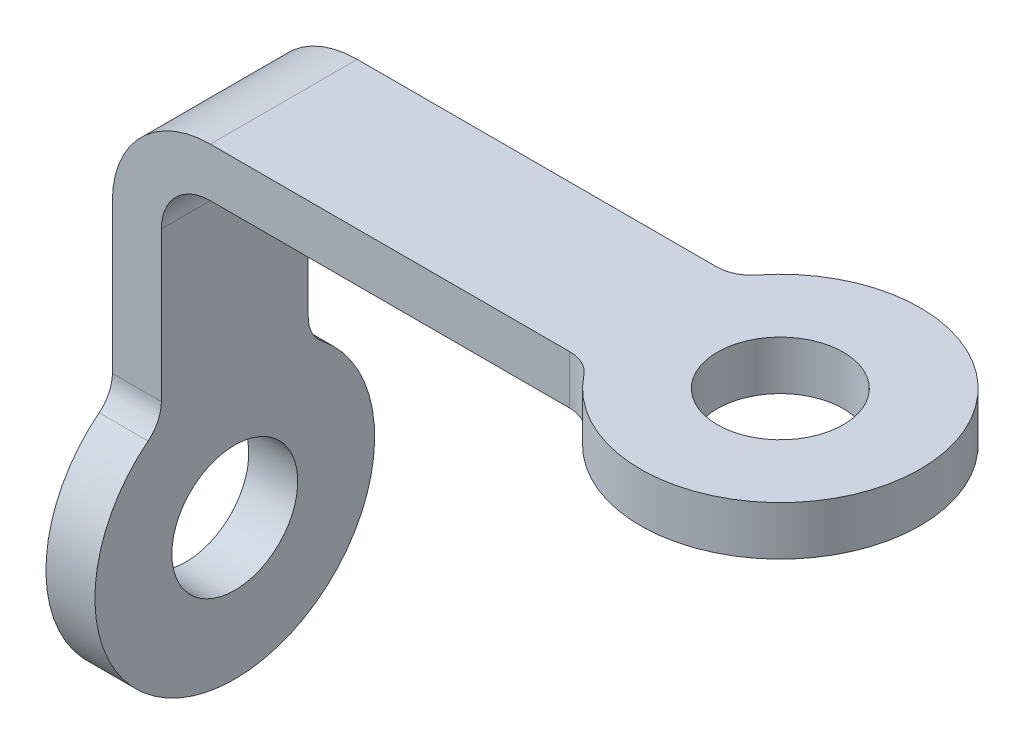
SolidWorks part; units mm, degrees
ref_plane "Front Plane" through (0, 0, 0) normal (0, 0, 1) x (1, 0, 0)
ref_plane "Top Plane" through (0, 0, 0) normal (0, 1, 0) x (1, 0, 0)
ref_plane "Right Plane" through (0, 0, 0) normal (1, 0, 0) x (0, 0, -1)
sketch "Sketch1" plane through (0, 0, 0) normal (0, 1, 0) x (1, 0, 0)
  line L0 (-19.615, 10.5) -> (-85, 10.5)
  line L1 (-19.615, -10.5) -> (-85, -10.5)
  line L2 (0, 0) -> (-86.4775, 0) construction
  line L3 (-85, 10.5) -> (-85, -10.5)
  circle A0 centre (0, 0) radius 9
  arc A1 (-15.692, -12.4) -> (-15.692, 12.4) centre (0, 0) ccw
  arc A2 (-19.615, -10.5) -> (-15.692, -12.4) centre (-19.615, -15.5) cw
  arc A3 (-19.615, 10.5) -> (-15.692, 12.4) centre (-19.615, 15.5) ccw
  point P3 (-68.0925, -10.5)
  dimension "D1" = 21
  dimension "D2" = 40
  dimension "D3" = 18
  dimension "D4" = 5
  dimension "D5" = 5
  dimension "D6" = 85
extrude "Boss-Extrude1" add sketch "Sketch1" against normal blind 7
sketch "Sketch2" plane through (0, -33.2388, -33.2388) normal (-1, 0, 0) x (0, -1, 0)
  line L0 (2.1462, 43.7388) -> (-33.2388, 43.7388)
  line L1 (2.1462, 22.7388) -> (-33.2388, 22.7388)
  line L2 (21.7612, 33.2388) -> (-86.4775, 33.2388) construction
  line L3 (-33.2388, 43.7388) -> (-33.2388, 22.7388)
  line L6 (-26.2388, 43.7388) -> (-33.2388, 43.7388) construction
  line L7 (-33.2388, 22.7388) -> (-33.2388, 43.7388) construction
  circle A0 centre (21.7612, 33.2388) radius 9
  arc A1 (6.0692, 20.8388) -> (6.0692, 45.6388) centre (21.7612, 33.2388) ccw
  arc A2 (2.1462, 22.7388) -> (6.0692, 20.8388) centre (2.1462, 17.7388) cw
  arc A3 (2.1462, 43.7388) -> (6.0692, 45.6388) centre (2.1462, 48.7388) ccw
  point P3 (-68.0925, -10.5)
  dimension "D1" = 21
  dimension "D2" = 40
  dimension "D3" = 18
  dimension "D4" = 5
  dimension "D5" = 5
  dimension "D6" = 55
extrude "Boss-Extrude2" add sketch "Sketch2" against normal blind 7 from offset 85
fillet "Fillet1" radius 14 1 edges at (-85, 0, 0)
fillet "Fillet2" radius 7 1 edges at (-78, -7, 0)
